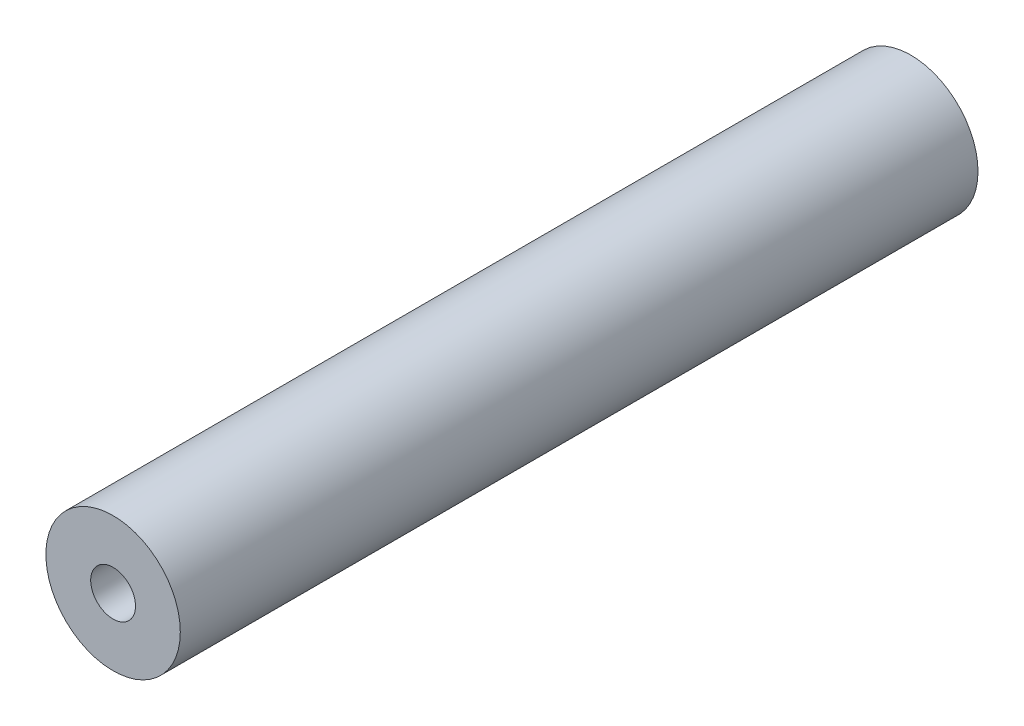
SolidWorks part; units mm, degrees
ref_plane "Alzado" through (0, 0, 0) normal (0, 0, 1) x (1, 0, 0)
ref_plane "Planta" through (0, 0, 0) normal (0, 1, 0) x (1, 0, 0)
ref_plane "Vista lateral" through (0, 0, 0) normal (1, 0, 0) x (0, 0, -1)
sketch "Croquis1" plane through (0, 0, 0) normal (0, 0, 1) x (1, 0, 0)
  circle A0 centre (0, 0) radius 7.5
extrude "Saliente-Extruir1" add sketch "Croquis1" against normal blind 89
sketch "Croquis2" plane through (0, 0, 0) normal (0, 0, 1) x (1, 0, 0)
  circle A0 centre (0, 0) radius 2.5
extrude "Cortar-Extruir1" cut sketch "Croquis2" against normal blind 89
